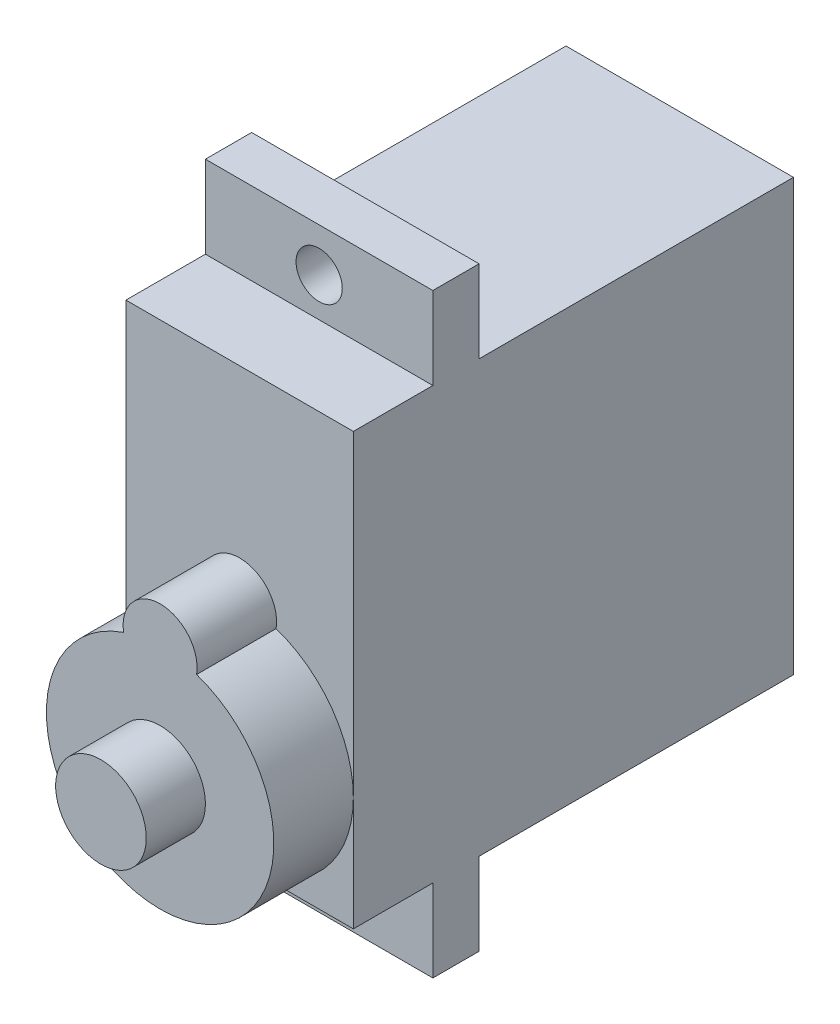
SolidWorks part; units mm, degrees
ref_plane "Plan de face" through (0, 0, 0) normal (0, 0, 1) x (1, 0, 0)
ref_plane "Plan de dessus" through (0, 0, 0) normal (0, 1, 0) x (1, 0, 0)
ref_plane "Plan de droite" through (0, 0, 0) normal (1, 0, 0) x (0, 0, -1)
sketch "Esquisse1" plane through (0, 0, 0) normal (0, 0, 1) x (1, 0, 0)
  line L1 (0, 0) -> (12.3, 0)
  line L2 (0, 0) -> (0, 23.3)
  line L3 (0, 23.3) -> (12.3, 23.3)
  line L4 (12.3, 0) -> (12.3, 23.3)
  dimension "D1" = 23.3
  dimension "D2" = 12.3
extrude "Boss.-Extru.1" add sketch "Esquisse1" along normal blind 17
sketch "Esquisse2" plane through (0, 0, 17) normal (0, 0, 1) x (1, 0, 0)
  line L0 (0, 23.3) -> (0, 0) construction
  line L1 (0, 27.75) -> (12.3, 27.75)
  line L2 (0, 27.75) -> (0, -4.45)
  line L3 (0, -4.45) -> (12.3, -4.45)
  line L4 (12.3, 27.75) -> (12.3, -4.45)
  line L5 (6.15, 27.75) -> (6.15, -4.45) construction
  line L6 (0, 11.65) -> (12.3, 11.65) construction
  circle A0 centre (6.15, 25.4) radius 1.25
  circle A1 centre (6.15, -2.1) radius 1.25
  point P4 (0, 11.65)
  dimension "D2" = 2.5
  dimension "D1" = 32.2
  dimension "D3" = 27.5
extrude "Boss.-Extru.2" add sketch "Esquisse2" along normal blind 2.5
sketch "Esquisse3" plane through (0, 0, 19.5) normal (0, 0, 1) x (1, 0, 0)
  line L0 (12.3, -4.45) -> (12.3, 27.75) construction
  line L1 (12.3, 23.3) -> (0, 23.3)
  line L2 (12.3, 23.3) -> (12.3, 0)
  line L3 (12.3, 0) -> (0, 0)
  line L4 (0, 23.3) -> (0, 0)
extrude "Boss.-Extru.3" add sketch "Esquisse3" along normal blind 4.3
sketch "Esquisse4" plane through (0, 0, 23.8) normal (0, 0, 1) x (1, 0, 0)
  line L0 (12.3, 0) -> (12.3, 23.3) construction
  line L1 (0, 23.3) -> (0, 0) construction
  line L2 (0, 0) -> (12.3, 0) construction
  arc A0 (4.1766, 11.9748) -> (8.1234, 11.9748) centre (6.15, 6.15) ccw
  arc A1 (8.1234, 11.9748) -> (4.1766, 11.9748) centre (6.15, 12.3) ccw
  dimension "D1" = 4
extrude "Boss.-Extru.4" add sketch "Esquisse4" along normal blind 4.3
sketch "Esquisse5" plane through (0, 0, 28.1) normal (0, 0, 1) x (1, 0, 0)
  circle A0 centre (6.15, 6.15) radius 2.45
  dimension "D1" = 4.9
extrude "Boss.-Extru.5" add sketch "Esquisse5" along normal blind 3.2
